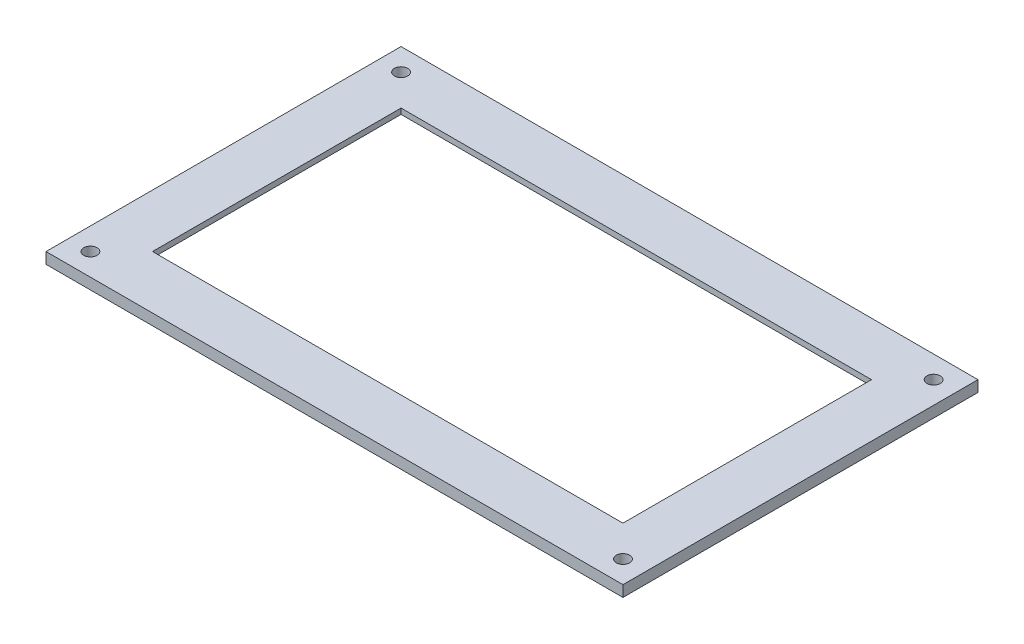
SolidWorks part; units mm, degrees
material "ABS PC"
ref_plane "Front Plane" through (0, 0, 0) normal (0, 0, 1) x (1, 0, 0)
ref_plane "Top Plane" through (0, 0, 0) normal (0, 1, 0) x (1, 0, 0)
ref_plane "Right Plane" through (0, 0, 0) normal (1, 0, 0) x (0, 0, -1)
sketch "Sketch1" plane through (0, 0, 0) normal (0, 1, 0) x (1, 0, 0)
  line L1 (0, 0) -> (130, 0)
  line L2 (0, 0) -> (0, 80)
  line L3 (0, 80) -> (130, 80)
  line L4 (130, 0) -> (130, 80)
  dimension "D1" = 130
  dimension "D2" = 80
extrude "Boss-Extrude1" add sketch "Sketch1" along normal blind 1.25
sketch "Sketch2" plane through (0, 0, 0) normal (0, -1, 0) x (1, 0, 0)
  line L0 (0, 0) -> (130, 0) construction
  line L1 (10, -10) -> (120, -10)
  line L2 (10, -10) -> (10, -70)
  line L3 (10, -70) -> (120, -70)
  line L4 (120, -10) -> (120, -70)
  line L5 (130, -80) -> (0, -80) construction
  line L6 (130, 0) -> (130, -80) construction
  line L7 (0, -80) -> (0, 0) construction
  dimension "D1" = 10
  dimension "D2" = 10
  dimension "D3" = 10
  dimension "D4" = 10
extrude "Cut-Extrude1" cut sketch "Sketch2" against normal through all
sketch "Sketch3" plane through (0, 1.25, 0) normal (0, 1, 0) x (1, 0, 0)
  line L0 (0, 80) -> (0, 0) construction
  line L1 (130, 80) -> (0, 80) construction
  line L2 (130, 0) -> (130, 80) construction
  line L3 (0, 0) -> (130, 0) construction
  circle A0 centre (5, 75) radius 1.5
  circle A1 centre (125, 75) radius 1.5
  circle A2 centre (125, 5) radius 1.5
  circle A3 centre (5, 5) radius 1.5
  dimension "D1" = 3
  dimension "D2" = 5
  dimension "D3" = 5
  dimension "D4" = 5
  dimension "D5" = 5
  dimension "D6" = 5
  dimension "D7" = 5
  dimension "D8" = 5
  dimension "D9" = 5
extrude "Cut-Extrude2" cut sketch "Sketch3" against normal through all
sketch "Sketch6" plane through (0, 1.25, 0) normal (0, 1, 0) x (1, 0, 0)
  line L4 (0, 80) -> (0, 0)
  line L5 (0, 0) -> (130, 0)
  line L6 (130, 0) -> (130, 80)
  line L7 (130, 80) -> (0, 80)
  line L8 (0, 80) -> (0, 0)
  line L9 (0, 0) -> (130, 0)
  line L10 (130, 0) -> (130, 80)
  line L11 (130, 80) -> (0, 80)
  line L13 (12, 68) -> (118, 68)
  line L14 (12, 68) -> (12, 12)
  line L15 (12, 12) -> (118, 12)
  line L16 (118, 68) -> (118, 12)
  dimension "D2" = 12
  dimension "D3" = 12
  dimension "D4" = 12
  dimension "D5" = 12
  dimension "D1" = 0
extrude "Boss-Extrude2" add sketch "Sketch6" along normal blind 1.25
sketch "Sketch7" plane through (0, 1.25, 0) normal (0, -1, 0) x (1, 0, 0)
  circle A1 centre (5, -75) radius 1.5
  circle A2 centre (5, -75) radius 1.5
  circle A3 centre (5, -5) radius 1.5
  circle A4 centre (5, -5) radius 1.5
  circle A5 centre (125, -5) radius 1.5
  circle A6 centre (125, -5) radius 1.5
  circle A7 centre (125, -75) radius 1.5
  circle A8 centre (125, -75) radius 1.5
  dimension "D1" = 0
  dimension "D2" = 0
  dimension "D3" = 0
  dimension "D4" = 0
extrude "Cut-Extrude4" cut sketch "Sketch7" against normal through all
